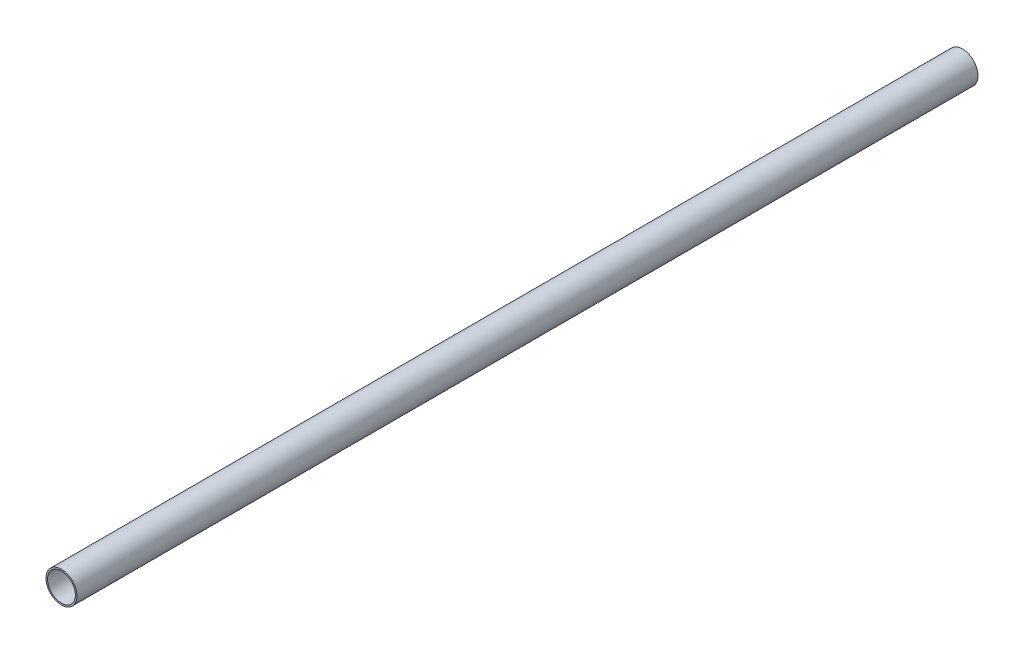
SolidWorks part; units mm, degrees
material "Copper-Cobalt-Beryllium alloy, UNS C17500"
ref_plane "Front Plane" through (0, 0, 0) normal (0, 0, 1) x (1, 0, 0)
ref_plane "Top Plane" through (0, 0, 0) normal (0, 1, 0) x (1, 0, 0)
ref_plane "Right Plane" through (0, 0, 0) normal (1, 0, 0) x (0, 0, -1)
sketch "Sketch1" plane through (0, 0, 0) normal (0, 0, 1) x (1, 0, 0)
  circle A0 centre (0, 0) radius 5
  dimension "D1" = 10
extrude "Boss-Extrude1" add sketch "Sketch1" along normal mid plane 291
shell "Shell1" thickness 0.5
